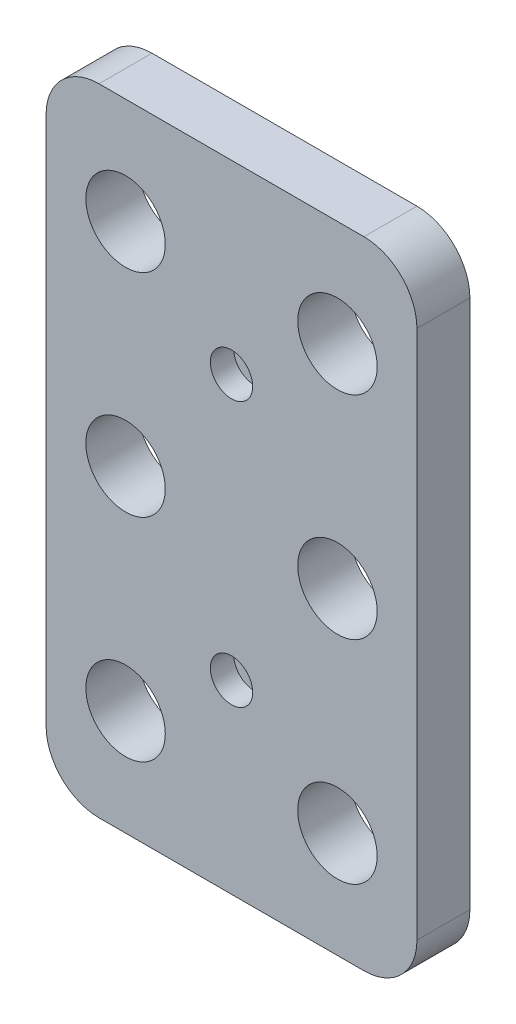
SolidWorks part; units mm, degrees
ref_plane "前视基准面" through (0, 0, 0) normal (0, 0, 1) x (1, 0, 0)
ref_plane "上视基准面" through (0, 0, 0) normal (0, 1, 0) x (1, 0, 0)
ref_plane "右视基准面" through (0, 0, 0) normal (1, 0, 0) x (0, 0, -1)
other "Configuration Table"
sketch "草图1" plane through (0, 0, 0) normal (0, 0, 1) x (1, 0, 0)
  line L0 (0, 60) -> (0, -60) construction
  line L1 (-25, -60) -> (25, -60)
  line L2 (-35, -50) -> (-35, 50)
  line L3 (-25, 60) -> (25, 60)
  line L4 (35, -50) -> (35, 50)
  line L5 (-35, -60) -> (35, 60) construction
  line L6 (-35, 60) -> (35, -60) construction
  line L7 (35, 0) -> (-35, 0) construction
  line L8 (35, 40) -> (-35, 40) construction
  arc A0 (-25, -60) -> (-35, -50) centre (-25, -50) cw
  arc A1 (25, -60) -> (35, -50) centre (25, -50) ccw
  arc A2 (25, 60) -> (35, 50) centre (25, 50) cw
  arc A3 (-35, 50) -> (-25, 60) centre (-25, 50) cw
  circle A4 centre (20, 40) radius 7.5
  circle A5 centre (20, 0) radius 7.5
  circle A6 centre (20, -40) radius 7.5
  circle A7 centre (-20, -40) radius 7.5
  circle A8 centre (-20, 0) radius 7.5
  circle A9 centre (-20, 40) radius 7.5
  circle A10 centre (0, 25) radius 2.25
  circle A11 centre (0, -25) radius 2.25
  point P0 (0, 0)
  dimension "D3" = 10
  dimension "D5" = 20
  dimension "D6" = 25
  dimension "D1" = 70
  dimension "D2" = 120
  dimension "D4" = 40
extrude "凸台-拉伸1" add sketch "草图1" along normal blind 10
sketch "草图2" plane through (0, 0, 10) normal (0, 0, 1) x (1, 0, 0)
  circle A0 centre (0, 25) radius 4
  circle A1 centre (0, -25) radius 4
extrude "切除-拉伸1" cut sketch "草图2" against normal blind 4.4
shell "抽壳1" thickness 3
